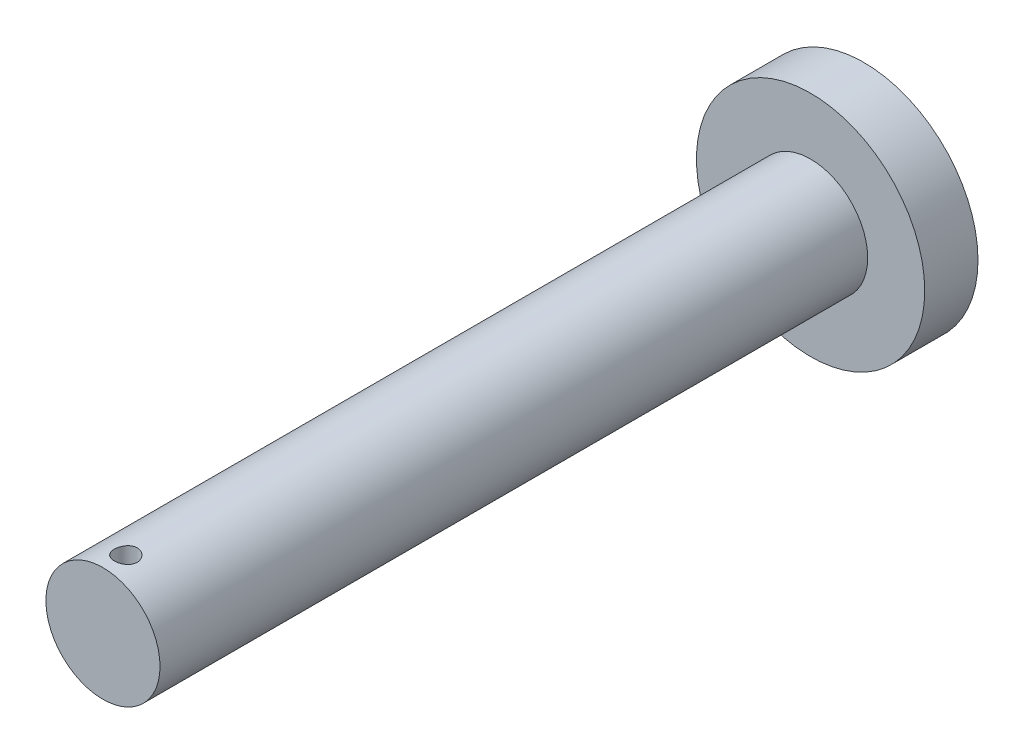
SolidWorks part; units mm, degrees
ref_plane "Front Plane" through (0, 0, 0) normal (0, 0, 1) x (1, 0, 0)
ref_plane "Top Plane" through (0, 0, 0) normal (0, 1, 0) x (1, 0, 0)
ref_plane "Right Plane" through (0, 0, 0) normal (1, 0, 0) x (0, 0, -1)
sketch "Sketch1" plane through (0, 0, 0) normal (0, 0, 1) x (1, 0, 0)
  circle A0 centre (0, 0) radius 30
extrude "Boss-Extrude1" add sketch "Sketch1" along normal blind 14
sketch "Sketch2" plane through (0, 0, 14) normal (0, 0, 1) x (1, 0, 0)
  circle A0 centre (0, 0) radius 15
extrude "Boss-Extrude2" add sketch "Sketch2" along normal blind 186
sketch "Sketch3" plane through (0, 0, 0) normal (0, 1, 0) x (1, 0, 0)
  circle A0 centre (0, -194) radius 3
extrude "Cut-Extrude1" cut sketch "Sketch3" against normal mid plane 186 contours A0
